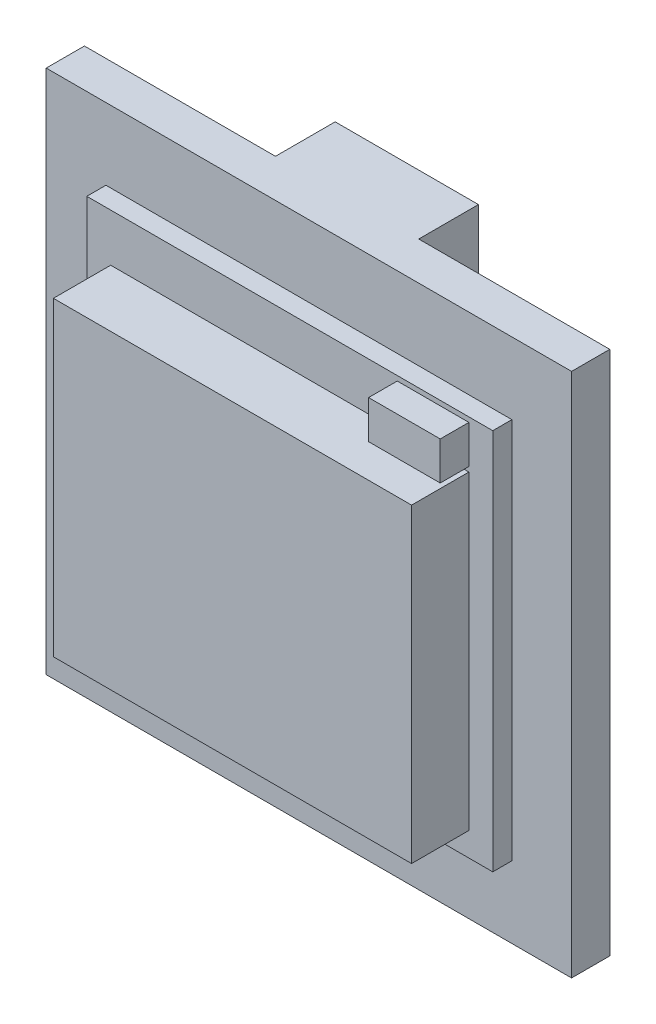
SolidWorks part; units mm, degrees
ref_plane "Front Plane" through (0, 0, 0) normal (0, 0, 1) x (1, 0, 0)
ref_plane "Top Plane" through (0, 0, 0) normal (0, 1, 0) x (1, 0, 0)
ref_plane "Right Plane" through (0, 0, 0) normal (1, 0, 0) x (0, 0, -1)
ref_plane "Plane1" through (0, 0, 10.6) normal (0, 0, 1) x (1, 0, 0)
sketch "Sketch1" plane through (0, 0, 10.6) normal (0, 0, 1) x (1, 0, 0)
  line L1 (15, 53) -> (21, 53)
  line L2 (15, 53) -> (15, 75)
  line L3 (15, 75) -> (21, 75)
  line L4 (21, 53) -> (21, 75)
  line L5 (15, 53) -> (21, 75) construction
  line L6 (15, 75) -> (21, 53) construction
  point P0 (18, 64)
extrude "Boss-Extrude1" add sketch "Sketch1" along normal blind 2.5
ref_plane "Plane2" through (0, 0, 13.1) normal (0, 0, 1) x (1, 0, 0)
sketch "Sketch2" plane through (0, 0, 13.1) normal (0, 0, 1) x (1, 0, 0)
  line L1 (7, 53) -> (29, 53)
  line L2 (7, 53) -> (7, 75)
  line L3 (7, 75) -> (29, 75)
  line L4 (29, 53) -> (29, 75)
  line L5 (7, 53) -> (29, 75) construction
  line L6 (7, 75) -> (29, 53) construction
  point P0 (18, 64)
extrude "Boss-Extrude2" add sketch "Sketch2" along normal blind 1.6
ref_plane "Plane3" through (0, 0, 14.7) normal (0, 0, 1) x (1, 0, 0)
sketch "Sketch3" plane through (0, 0, 14.7) normal (0, 0, 1) x (1, 0, 0)
  line L1 (9.5, 56) -> (26.5, 56)
  line L2 (9.5, 56) -> (9.5, 72)
  line L3 (9.5, 72) -> (26.5, 72)
  line L4 (26.5, 56) -> (26.5, 72)
  line L5 (9.5, 56) -> (26.5, 72) construction
  line L6 (9.5, 72) -> (26.5, 56) construction
  point P0 (18, 64)
extrude "Boss-Extrude3" add sketch "Sketch3" along normal blind 0.8
ref_plane "Plane4" through (0, 0, 15.5) normal (0, 0, 1) x (1, 0, 0)
sketch "Sketch4" plane through (0, 0, 15.5) normal (0, 0, 1) x (1, 0, 0)
  line L1 (10.5, 57) -> (25.5, 57)
  line L2 (10.5, 57) -> (10.5, 70)
  line L3 (10.5, 70) -> (25.5, 70)
  line L4 (25.5, 57) -> (25.5, 70)
  line L5 (10.5, 57) -> (25.5, 70) construction
  line L6 (10.5, 70) -> (25.5, 57) construction
  point P0 (18, 63.5)
extrude "Boss-Extrude4" add sketch "Sketch4" along normal blind 2.4
sketch "Sketch5" plane through (0, 0, 15.5) normal (0, 0, 1) x (1, 0, 0)
  line L1 (22.5, 70.2) -> (25.5, 70.2)
  line L2 (22.5, 70.2) -> (22.5, 71.8)
  line L3 (22.5, 71.8) -> (25.5, 71.8)
  line L4 (25.5, 70.2) -> (25.5, 71.8)
  line L5 (22.5, 70.2) -> (25.5, 71.8) construction
  line L6 (22.5, 71.8) -> (25.5, 70.2) construction
  point P0 (24, 71)
extrude "Boss-Extrude5" add sketch "Sketch5" along normal blind 1.2
